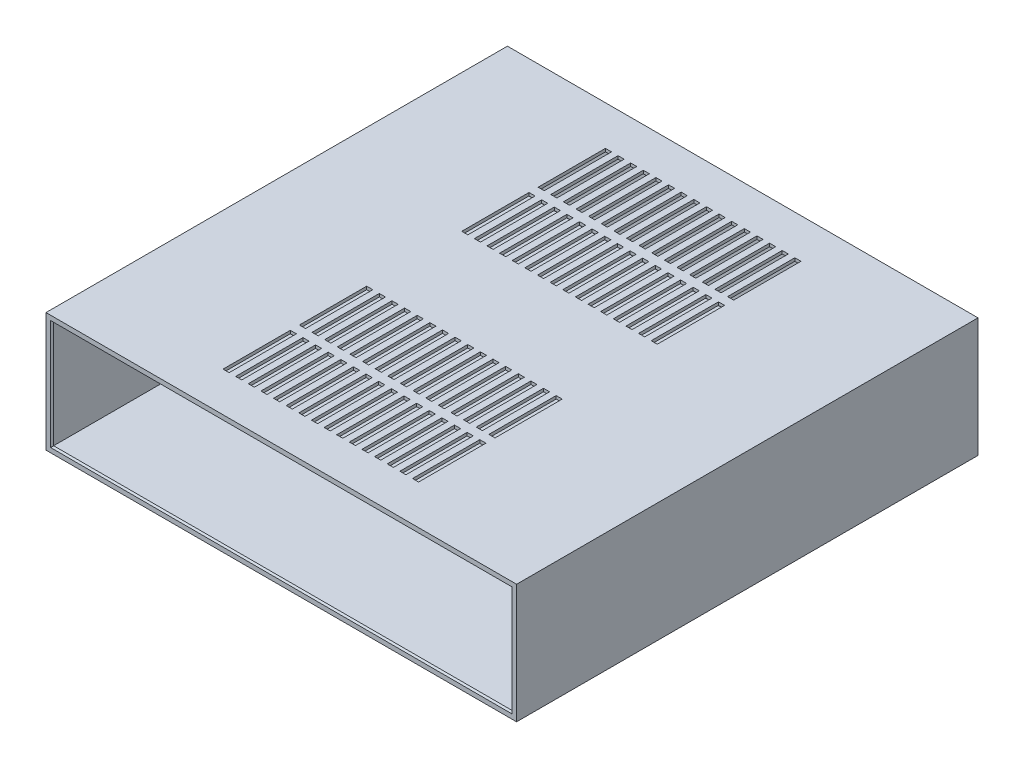
SolidWorks part; units mm, degrees
ref_plane "Спереди" through (0, 0, 0) normal (0, 0, 1) x (1, 0, 0)
ref_plane "Сверху" through (0, 0, 0) normal (0, 1, 0) x (1, 0, 0)
ref_plane "Справа" through (0, 0, 0) normal (1, 0, 0) x (0, 0, -1)
sketch "Эскиз1" plane through (0, 0, 0) normal (0, 0, 1) x (1, 0, 0)
  line L1 (-150, 35) -> (150, 35)
  line L2 (-150, 35) -> (-150, -35)
  line L3 (-150, -35) -> (150, -35)
  line L4 (150, 35) -> (150, -35)
  line L5 (-154, 39) -> (154, 39)
  line L6 (-154, 39) -> (-154, -39)
  line L7 (-154, -39) -> (154, -39)
  line L8 (154, 39) -> (154, -39)
  dimension "D1" = 4
  dimension "D2" = 4
  dimension "D3" = 4
  dimension "D4" = 4
extrude "Бобышка-Вытянуть1" add sketch "Эскиз1" along normal blind 2 and the other way blind 300
chamfer "Фаска1" distance 1 angle 45 4 edges at (-150, 0, 2) (0, -35, 2) (150, 0, 2) (0, 35, 2)
sketch "Дырки в корпусе" plane through (0, 0, 0) normal (0, 1, 0) x (1, 0, 0)
  line L0 (-55.7333, 67.9019) -> (-55.7333, 23.8663)
  line L1 (-64, 67.9019) -> (-60, 67.9019)
  line L2 (-64, 67.9019) -> (-64, 23.8663)
  line L3 (-64, 23.8663) -> (-60, 23.8663)
  line L4 (-60, 67.9019) -> (-60, 23.8663)
  line L5 (-55.7333, 67.9019) -> (-51.7333, 67.9019)
  line L6 (-51.7333, 67.9019) -> (-51.7333, 23.8663)
  line L7 (-55.7333, 23.8663) -> (-51.7333, 23.8663)
  line L8 (-47.4667, 67.9019) -> (-47.4667, 23.8663)
  line L9 (-47.4667, 67.9019) -> (-43.4667, 67.9019)
  line L10 (-43.4667, 67.9019) -> (-43.4667, 23.8663)
  line L11 (-47.4667, 23.8663) -> (-43.4667, 23.8663)
  line L12 (-39.2, 67.9019) -> (-39.2, 23.8663)
  line L13 (-39.2, 67.9019) -> (-35.2, 67.9019)
  line L14 (-35.2, 67.9019) -> (-35.2, 23.8663)
  line L15 (-39.2, 23.8663) -> (-35.2, 23.8663)
  line L16 (-30.9333, 67.9019) -> (-30.9333, 23.8663)
  line L17 (-30.9333, 67.9019) -> (-26.9333, 67.9019)
  line L18 (-26.9333, 67.9019) -> (-26.9333, 23.8663)
  line L19 (-30.9333, 23.8663) -> (-26.9333, 23.8663)
  line L20 (-22.6667, 67.9019) -> (-22.6667, 23.8663)
  line L21 (-22.6667, 67.9019) -> (-18.6667, 67.9019)
  line L22 (-18.6667, 67.9019) -> (-18.6667, 23.8663)
  line L23 (-22.6667, 23.8663) -> (-18.6667, 23.8663)
  line L24 (-14.4, 67.9019) -> (-14.4, 23.8663)
  line L25 (-14.4, 67.9019) -> (-10.4, 67.9019)
  line L26 (-10.4, 67.9019) -> (-10.4, 23.8663)
  line L27 (-14.4, 23.8663) -> (-10.4, 23.8663)
  line L28 (-6.1333, 67.9019) -> (-6.1333, 23.8663)
  line L29 (-6.1333, 67.9019) -> (-2.1333, 67.9019)
  line L30 (-2.1333, 67.9019) -> (-2.1333, 23.8663)
  line L31 (-6.1333, 23.8663) -> (-2.1333, 23.8663)
  line L32 (2.1333, 67.9019) -> (2.1333, 23.8663)
  line L33 (2.1333, 67.9019) -> (6.1333, 67.9019)
  line L34 (6.1333, 67.9019) -> (6.1333, 23.8663)
  line L35 (2.1333, 23.8663) -> (6.1333, 23.8663)
  line L36 (10.4, 67.9019) -> (10.4, 23.8663)
  line L37 (10.4, 67.9019) -> (14.4, 67.9019)
  line L38 (14.4, 67.9019) -> (14.4, 23.8663)
  line L39 (10.4, 23.8663) -> (14.4, 23.8663)
  line L40 (18.6667, 67.9019) -> (18.6667, 23.8663)
  line L41 (18.6667, 67.9019) -> (22.6667, 67.9019)
  line L42 (22.6667, 67.9019) -> (22.6667, 23.8663)
  line L43 (18.6667, 23.8663) -> (22.6667, 23.8663)
  line L44 (26.9333, 67.9019) -> (26.9333, 23.8663)
  line L45 (26.9333, 67.9019) -> (30.9333, 67.9019)
  line L46 (30.9333, 67.9019) -> (30.9333, 23.8663)
  line L47 (26.9333, 23.8663) -> (30.9333, 23.8663)
  line L48 (35.2, 67.9019) -> (35.2, 23.8663)
  line L49 (35.2, 67.9019) -> (39.2, 67.9019)
  line L50 (39.2, 67.9019) -> (39.2, 23.8663)
  line L51 (35.2, 23.8663) -> (39.2, 23.8663)
  line L52 (43.4667, 67.9019) -> (43.4667, 23.8663)
  line L53 (43.4667, 67.9019) -> (47.4667, 67.9019)
  line L54 (47.4667, 67.9019) -> (47.4667, 23.8663)
  line L55 (43.4667, 23.8663) -> (47.4667, 23.8663)
  line L56 (51.7333, 67.9019) -> (51.7333, 23.8663)
  line L57 (51.7333, 67.9019) -> (55.7333, 67.9019)
  line L58 (55.7333, 67.9019) -> (55.7333, 23.8663)
  line L59 (51.7333, 23.8663) -> (55.7333, 23.8663)
  line L60 (60, 67.9019) -> (60, 23.8663)
  line L61 (60, 67.9019) -> (64, 67.9019)
  line L62 (64, 67.9019) -> (64, 23.8663)
  line L63 (60, 23.8663) -> (64, 23.8663)
  line L64 (-154, 300) -> (-154, -2) construction
  line L65 (154, 300) -> (154, -2) construction
  line L66 (-55.7333, 117.9019) -> (-55.7333, 73.8663)
  line L67 (-64, 117.9019) -> (-60, 117.9019)
  line L68 (-64, 117.9019) -> (-64, 73.8663)
  line L69 (-64, 73.8663) -> (-60, 73.8663)
  line L70 (-60, 117.9019) -> (-60, 73.8663)
  line L71 (-55.7333, 117.9019) -> (-51.7333, 117.9019)
  line L72 (-51.7333, 117.9019) -> (-51.7333, 73.8663)
  line L73 (-55.7333, 73.8663) -> (-51.7333, 73.8663)
  line L74 (-47.4667, 117.9019) -> (-47.4667, 73.8663)
  line L75 (-47.4667, 117.9019) -> (-43.4667, 117.9019)
  line L76 (-43.4667, 117.9019) -> (-43.4667, 73.8663)
  line L77 (-47.4667, 73.8663) -> (-43.4667, 73.8663)
  line L78 (-39.2, 117.9019) -> (-39.2, 73.8663)
  line L79 (-39.2, 117.9019) -> (-35.2, 117.9019)
  line L80 (-35.2, 117.9019) -> (-35.2, 73.8663)
  line L81 (-39.2, 73.8663) -> (-35.2, 73.8663)
  line L82 (-30.9333, 117.9019) -> (-30.9333, 73.8663)
  line L83 (-30.9333, 117.9019) -> (-26.9333, 117.9019)
  line L84 (-26.9333, 117.9019) -> (-26.9333, 73.8663)
  line L85 (-30.9333, 73.8663) -> (-26.9333, 73.8663)
  line L86 (-22.6667, 117.9019) -> (-22.6667, 73.8663)
  line L87 (-22.6667, 117.9019) -> (-18.6667, 117.9019)
  line L88 (-18.6667, 117.9019) -> (-18.6667, 73.8663)
  line L89 (-22.6667, 73.8663) -> (-18.6667, 73.8663)
  line L90 (-14.4, 117.9019) -> (-14.4, 73.8663)
  line L91 (-14.4, 117.9019) -> (-10.4, 117.9019)
  line L92 (-10.4, 117.9019) -> (-10.4, 73.8663)
  line L93 (-14.4, 73.8663) -> (-10.4, 73.8663)
  line L94 (-6.1333, 117.9019) -> (-6.1333, 73.8663)
  line L95 (-6.1333, 117.9019) -> (-2.1333, 117.9019)
  line L96 (-2.1333, 117.9019) -> (-2.1333, 73.8663)
  line L97 (-6.1333, 73.8663) -> (-2.1333, 73.8663)
  line L98 (2.1333, 117.9019) -> (2.1333, 73.8663)
  line L99 (2.1333, 117.9019) -> (6.1333, 117.9019)
  line L100 (6.1333, 117.9019) -> (6.1333, 73.8663)
  line L101 (2.1333, 73.8663) -> (6.1333, 73.8663)
  line L102 (10.4, 117.9019) -> (10.4, 73.8663)
  line L103 (10.4, 117.9019) -> (14.4, 117.9019)
  line L104 (14.4, 117.9019) -> (14.4, 73.8663)
  line L105 (10.4, 73.8663) -> (14.4, 73.8663)
  line L106 (18.6667, 117.9019) -> (18.6667, 73.8663)
  line L107 (18.6667, 117.9019) -> (22.6667, 117.9019)
  line L108 (22.6667, 117.9019) -> (22.6667, 73.8663)
  line L109 (18.6667, 73.8663) -> (22.6667, 73.8663)
  line L110 (26.9333, 117.9019) -> (26.9333, 73.8663)
  line L111 (26.9333, 117.9019) -> (30.9333, 117.9019)
  line L112 (30.9333, 117.9019) -> (30.9333, 73.8663)
  line L113 (26.9333, 73.8663) -> (30.9333, 73.8663)
  line L114 (35.2, 117.9019) -> (35.2, 73.8663)
  line L115 (35.2, 117.9019) -> (39.2, 117.9019)
  line L116 (39.2, 117.9019) -> (39.2, 73.8663)
  line L117 (35.2, 73.8663) -> (39.2, 73.8663)
  line L118 (43.4667, 117.9019) -> (43.4667, 73.8663)
  line L119 (43.4667, 117.9019) -> (47.4667, 117.9019)
  line L120 (47.4667, 117.9019) -> (47.4667, 73.8663)
  line L121 (43.4667, 73.8663) -> (47.4667, 73.8663)
  line L122 (51.7333, 117.9019) -> (51.7333, 73.8663)
  line L123 (51.7333, 117.9019) -> (55.7333, 117.9019)
  line L124 (55.7333, 117.9019) -> (55.7333, 73.8663)
  line L125 (51.7333, 73.8663) -> (55.7333, 73.8663)
  line L126 (60, 117.9019) -> (60, 73.8663)
  line L127 (60, 117.9019) -> (64, 117.9019)
  line L128 (64, 117.9019) -> (64, 73.8663)
  line L129 (60, 73.8663) -> (64, 73.8663)
  line L130 (-55.7333, 224.13) -> (-55.7333, 180.0944)
  line L131 (-64, 224.13) -> (-60, 224.13)
  line L132 (-64, 224.13) -> (-64, 180.0944)
  line L133 (-64, 180.0944) -> (-60, 180.0944)
  line L134 (-60, 224.13) -> (-60, 180.0944)
  line L135 (-55.7333, 224.13) -> (-51.7333, 224.13)
  line L136 (-51.7333, 224.13) -> (-51.7333, 180.0944)
  line L137 (-55.7333, 180.0944) -> (-51.7333, 180.0944)
  line L138 (-47.4667, 224.13) -> (-47.4667, 180.0944)
  line L139 (-47.4667, 224.13) -> (-43.4667, 224.13)
  line L140 (-43.4667, 224.13) -> (-43.4667, 180.0944)
  line L141 (-47.4667, 180.0944) -> (-43.4667, 180.0944)
  line L142 (-39.2, 224.13) -> (-39.2, 180.0944)
  line L143 (-39.2, 224.13) -> (-35.2, 224.13)
  line L144 (-35.2, 224.13) -> (-35.2, 180.0944)
  line L145 (-39.2, 180.0944) -> (-35.2, 180.0944)
  line L146 (-30.9333, 224.13) -> (-30.9333, 180.0944)
  line L147 (-30.9333, 224.13) -> (-26.9333, 224.13)
  line L148 (-26.9333, 224.13) -> (-26.9333, 180.0944)
  line L149 (-30.9333, 180.0944) -> (-26.9333, 180.0944)
  line L150 (-22.6667, 224.13) -> (-22.6667, 180.0944)
  line L151 (-22.6667, 224.13) -> (-18.6667, 224.13)
  line L152 (-18.6667, 224.13) -> (-18.6667, 180.0944)
  line L153 (-22.6667, 180.0944) -> (-18.6667, 180.0944)
  line L154 (-14.4, 224.13) -> (-14.4, 180.0944)
  line L155 (-14.4, 224.13) -> (-10.4, 224.13)
  line L156 (-10.4, 224.13) -> (-10.4, 180.0944)
  line L157 (-14.4, 180.0944) -> (-10.4, 180.0944)
  line L158 (-6.1333, 224.13) -> (-6.1333, 180.0944)
  line L159 (-6.1333, 224.13) -> (-2.1333, 224.13)
  line L160 (-2.1333, 224.13) -> (-2.1333, 180.0944)
  line L161 (-6.1333, 180.0944) -> (-2.1333, 180.0944)
  line L162 (2.1333, 224.13) -> (2.1333, 180.0944)
  line L163 (2.1333, 224.13) -> (6.1333, 224.13)
  line L164 (6.1333, 224.13) -> (6.1333, 180.0944)
  line L165 (2.1333, 180.0944) -> (6.1333, 180.0944)
  line L166 (10.4, 224.13) -> (10.4, 180.0944)
  line L167 (10.4, 224.13) -> (14.4, 224.13)
  line L168 (14.4, 224.13) -> (14.4, 180.0944)
  line L169 (10.4, 180.0944) -> (14.4, 180.0944)
  line L170 (18.6667, 224.13) -> (18.6667, 180.0944)
  line L171 (18.6667, 224.13) -> (22.6667, 224.13)
  line L172 (22.6667, 224.13) -> (22.6667, 180.0944)
  line L173 (18.6667, 180.0944) -> (22.6667, 180.0944)
  line L174 (26.9333, 224.13) -> (26.9333, 180.0944)
  line L175 (26.9333, 224.13) -> (30.9333, 224.13)
  line L176 (30.9333, 224.13) -> (30.9333, 180.0944)
  line L177 (26.9333, 180.0944) -> (30.9333, 180.0944)
  line L178 (35.2, 224.13) -> (35.2, 180.0944)
  line L179 (35.2, 224.13) -> (39.2, 224.13)
  line L180 (39.2, 224.13) -> (39.2, 180.0944)
  line L181 (35.2, 180.0944) -> (39.2, 180.0944)
  line L182 (43.4667, 224.13) -> (43.4667, 180.0944)
  line L183 (43.4667, 224.13) -> (47.4667, 224.13)
  line L184 (47.4667, 224.13) -> (47.4667, 180.0944)
  line L185 (43.4667, 180.0944) -> (47.4667, 180.0944)
  line L186 (51.7333, 224.13) -> (51.7333, 180.0944)
  line L187 (51.7333, 224.13) -> (55.7333, 224.13)
  line L188 (55.7333, 224.13) -> (55.7333, 180.0944)
  line L189 (51.7333, 180.0944) -> (55.7333, 180.0944)
  line L190 (60, 224.13) -> (60, 180.0944)
  line L191 (60, 224.13) -> (64, 224.13)
  line L192 (64, 224.13) -> (64, 180.0944)
  line L193 (60, 180.0944) -> (64, 180.0944)
  line L194 (-55.7333, 274.13) -> (-55.7333, 230.0944)
  line L195 (-64, 274.13) -> (-60, 274.13)
  line L196 (-64, 274.13) -> (-64, 230.0944)
  line L197 (-64, 230.0944) -> (-60, 230.0944)
  line L198 (-60, 274.13) -> (-60, 230.0944)
  line L199 (-55.7333, 274.13) -> (-51.7333, 274.13)
  line L200 (-51.7333, 274.13) -> (-51.7333, 230.0944)
  line L201 (-55.7333, 230.0944) -> (-51.7333, 230.0944)
  line L202 (-47.4667, 274.13) -> (-47.4667, 230.0944)
  line L203 (-47.4667, 274.13) -> (-43.4667, 274.13)
  line L204 (-43.4667, 274.13) -> (-43.4667, 230.0944)
  line L205 (-47.4667, 230.0944) -> (-43.4667, 230.0944)
  line L206 (-39.2, 274.13) -> (-39.2, 230.0944)
  line L207 (-39.2, 274.13) -> (-35.2, 274.13)
  line L208 (-35.2, 274.13) -> (-35.2, 230.0944)
  line L209 (-39.2, 230.0944) -> (-35.2, 230.0944)
  line L210 (-30.9333, 274.13) -> (-30.9333, 230.0944)
  line L211 (-30.9333, 274.13) -> (-26.9333, 274.13)
  line L212 (-26.9333, 274.13) -> (-26.9333, 230.0944)
  line L213 (-30.9333, 230.0944) -> (-26.9333, 230.0944)
  line L214 (-22.6667, 274.13) -> (-22.6667, 230.0944)
  line L215 (-22.6667, 274.13) -> (-18.6667, 274.13)
  line L216 (-18.6667, 274.13) -> (-18.6667, 230.0944)
  line L217 (-22.6667, 230.0944) -> (-18.6667, 230.0944)
  line L218 (-14.4, 274.13) -> (-14.4, 230.0944)
  line L219 (-14.4, 274.13) -> (-10.4, 274.13)
  line L220 (-10.4, 274.13) -> (-10.4, 230.0944)
  line L221 (-14.4, 230.0944) -> (-10.4, 230.0944)
  line L222 (-6.1333, 274.13) -> (-6.1333, 230.0944)
  line L223 (-6.1333, 274.13) -> (-2.1333, 274.13)
  line L224 (-2.1333, 274.13) -> (-2.1333, 230.0944)
  line L225 (-6.1333, 230.0944) -> (-2.1333, 230.0944)
  line L226 (2.1333, 274.13) -> (2.1333, 230.0944)
  line L227 (2.1333, 274.13) -> (6.1333, 274.13)
  line L228 (6.1333, 274.13) -> (6.1333, 230.0944)
  line L229 (2.1333, 230.0944) -> (6.1333, 230.0944)
  line L230 (10.4, 274.13) -> (10.4, 230.0944)
  line L231 (10.4, 274.13) -> (14.4, 274.13)
  line L232 (14.4, 274.13) -> (14.4, 230.0944)
  line L233 (10.4, 230.0944) -> (14.4, 230.0944)
  line L234 (18.6667, 274.13) -> (18.6667, 230.0944)
  line L235 (18.6667, 274.13) -> (22.6667, 274.13)
  line L236 (22.6667, 274.13) -> (22.6667, 230.0944)
  line L237 (18.6667, 230.0944) -> (22.6667, 230.0944)
  line L238 (26.9333, 274.13) -> (26.9333, 230.0944)
  line L239 (26.9333, 274.13) -> (30.9333, 274.13)
  line L240 (30.9333, 274.13) -> (30.9333, 230.0944)
  line L241 (26.9333, 230.0944) -> (30.9333, 230.0944)
  line L242 (35.2, 274.13) -> (35.2, 230.0944)
  line L243 (35.2, 274.13) -> (39.2, 274.13)
  line L244 (39.2, 274.13) -> (39.2, 230.0944)
  line L245 (35.2, 230.0944) -> (39.2, 230.0944)
  line L246 (43.4667, 274.13) -> (43.4667, 230.0944)
  line L247 (43.4667, 274.13) -> (47.4667, 274.13)
  line L248 (47.4667, 274.13) -> (47.4667, 230.0944)
  line L249 (43.4667, 230.0944) -> (47.4667, 230.0944)
  line L250 (51.7333, 274.13) -> (51.7333, 230.0944)
  line L251 (51.7333, 274.13) -> (55.7333, 274.13)
  line L252 (55.7333, 274.13) -> (55.7333, 230.0944)
  line L253 (51.7333, 230.0944) -> (55.7333, 230.0944)
  line L254 (60, 274.13) -> (60, 230.0944)
  line L255 (60, 274.13) -> (64, 274.13)
  line L256 (64, 274.13) -> (64, 230.0944)
  line L257 (60, 230.0944) -> (64, 230.0944)
  line L258 (154, -2) -> (-154, -2) construction
  line L259 (154, 300) -> (-154, 300) construction
  dimension "D2" = 4
  dimension "D3" = 90
  dimension "D4" = 90
  dimension "D7" = 25.8663
  dimension "D8" = 25.87
  dimension "D1" = 16
  dimension "D5" = 2
  dimension "D6" = 2
extrude "Вырез-Вытянуть3" cut sketch "Дырки в корпусе" against normal blind 0.0001 and the other way up to surface
sketch "Эскиз2" plane through (0, 35, 0) normal (0, -1, 0) x (1, 0, 0)
  line L0 (-64, -274.13) -> (-64, -230.0944) construction
  line L1 (-84, -294.13) -> (84, -294.13)
  line L2 (-84, -294.13) -> (-84, -3.8663)
  line L3 (-84, -3.8663) -> (84, -3.8663)
  line L4 (84, -294.13) -> (84, -3.8663)
  line L5 (64, -230.0944) -> (64, -274.13) construction
  line L6 (10.4, -274.13) -> (14.4, -274.13) construction
  dimension "D1" = 20
  dimension "D2" = 20
  dimension "D3" = 20
  dimension "D4" = 20
extrude "Вырез-Вытянуть4" cut sketch "Эскиз2" against normal blind 2
sketch "Эскиз3" plane through (150, 0, 0) normal (-1, 0, 0) x (0, 0, 1)
  line L0 (-300, -35) -> (1, -35) construction
  line L1 (-300, 35) -> (-296, 35)
  line L2 (-300, 35) -> (-300, -35)
  line L3 (-300, -35) -> (-296, -35)
  line L4 (-296, 35) -> (-296, -35)
  dimension "D1" = 4
extrude "Бобышка-Вытянуть2" add sketch "Эскиз3" along normal up to next
